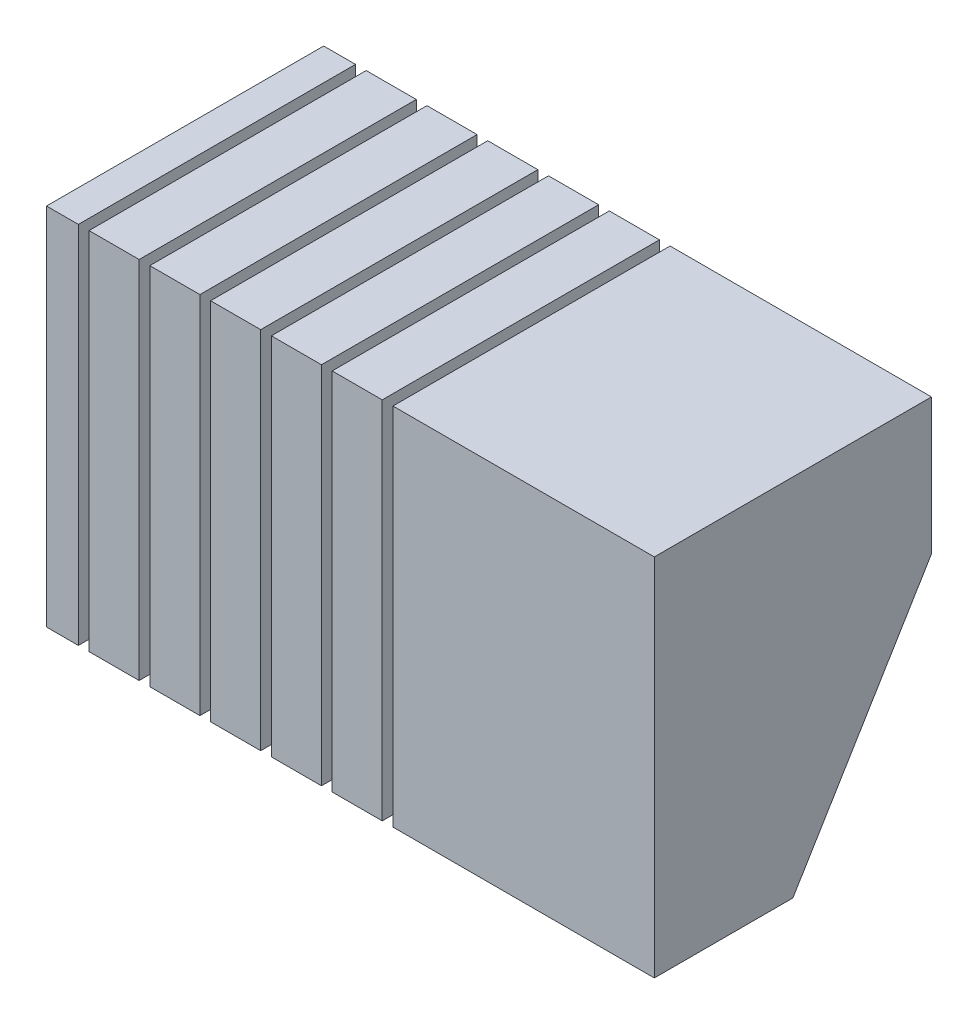
SolidWorks part; units mm, degrees
other "零件2"
other "零件7"
other "零件1"
other "零件3"
other "复制-零件2-3"
other "复制-零件2-2"
other "复制-零件2"
ref_plane "前视基准面" through (0, 0, 0) normal (0, 0, 1) x (1, 0, 0)
ref_plane "上视基准面" through (0, 0, 0) normal (0, 1, 0) x (1, 0, 0)
ref_plane "右视基准面" through (0, 0, 0) normal (1, 0, 0) x (0, 0, -1)
sketch "Sketch1" plane through (0, 0, 0) normal (0, 0, 1) x (1, 0, 0)
  line L1 (-125, -75) -> (125, -75)
  line L2 (-125, -75) -> (-125, 75)
  line L3 (-125, 75) -> (125, 75)
  line L4 (125, -75) -> (125, 75)
  line L5 (-125, -75) -> (125, 75) construction
  line L6 (-125, 75) -> (125, -75) construction
  point P0 (0, 0)
  dimension "D1" = 250
  dimension "D2" = 150
extrude "Boss-Extrude1" add sketch "Sketch1" along normal blind 114
sketch "sketchCenterLine" plane through (0, 0, 114) normal (0, 0, 1) x (1, 0, 0)
  line L0 (0, 0) -> (-160.1488, 0) construction
  line L1 (-170, 12.5) -> (-115, 12.5)
  line L2 (-97.3223, 19.8223) -> (-69.467, 47.6777)
  line L3 (-51.7893, 55) -> (70, 55)
  line L4 (95, 30) -> (95, -30)
  line L5 (70, -55) -> (-51.7893, -55)
  line L6 (-69.467, -47.6777) -> (-97.3223, -19.8223)
  line L7 (-115, -12.5) -> (-170, -12.5)
  line L8 (-125, 75) -> (-125, -75) construction
  arc A0 (70, -55) -> (95, -30) centre (70, -30) ccw
  arc A1 (95, 30) -> (70, 55) centre (70, 30) ccw
  arc A2 (-115, 12.5) -> (-97.3223, 19.8223) centre (-115, 37.5) ccw
  arc A3 (-97.3223, -19.8223) -> (-115, -12.5) centre (-115, -37.5) ccw
  arc A4 (-51.7893, -55) -> (-69.467, -47.6777) centre (-51.7893, -30) cw
  arc A5 (-69.467, 47.6777) -> (-51.7893, 55) centre (-51.7893, 30) cw
  point P24 (-62.1447, -55)
  point P27 (-62.1447, 55)
  dimension "D1" = 25
  dimension "D2" = 25
  dimension "D8" = 10
  dimension "D3" = 95
  dimension "D4" = 110
  dimension "D5" = 25
  dimension "D6" = 45
  dimension "D7" = 45
sketch3d "3DSketch1"
  line L0 (125, -75, 114) -> (125, -75, 0) construction
  line L1 (125, -75, 0) -> (125, 75, 0) construction
  line L2 (-125, -75, 0) -> (125, -75, 0) construction
  point P0 (125, -75, 57)
  point P1 (125, 19.0618, 0)
  point P4 (42.2925, -75, 0)
ref_plane "Plane1" through (27.9069, -24.5383, -40.4932) normal (-0.5078, 0.4465, 0.7368) x (0.8615, 0.2632, 0.4343)
sketch "Sketch4" plane through (27.9069, -24.5383, -40.4932) normal (-0.5078, 0.4465, 0.7368) x (0.8615, 0.2632, 0.4343)
  line L1 (-16.3307, -143.8321) -> (142.4953, -143.8321)
  line L2 (-16.3307, -143.8321) -> (-16.3307, 25.2667)
  line L3 (-16.3307, 25.2667) -> (142.4953, 25.2667)
  line L4 (142.4953, -143.8321) -> (142.4953, 25.2667)
extrude "Cut-Extrude1" cut sketch "Sketch4" against normal blind 114
sketch "Sketch5" plane through (0, -75, 0) normal (0, -1, 0) x (1, 0, 0)
  line L1 (-111.911, -16.0572) -> (-107.5129, -16.0572)
  line L2 (-111.911, -16.0572) -> (-111.911, 130.5458)
  line L3 (-111.911, 130.5458) -> (-107.5129, 130.5458)
  line L4 (-107.5129, -16.0572) -> (-107.5129, 130.5458)
extrude "Cut-Extrude2" cut sketch "Sketch5" against normal through all
pattern_linear "LPattern1" count 6 spacing 25 along (1, 0, 0) of "Cut-Extrude2"
sketch3d "3DSketch2"
  line L0 (-125, 14.4685, 57.4595) -> (-213.849, 12.5554, 107.8732)
  point P0 (-125, 14.4685, 57.4595)
  point P3 (-213.849, 12.5554, 107.8732)
